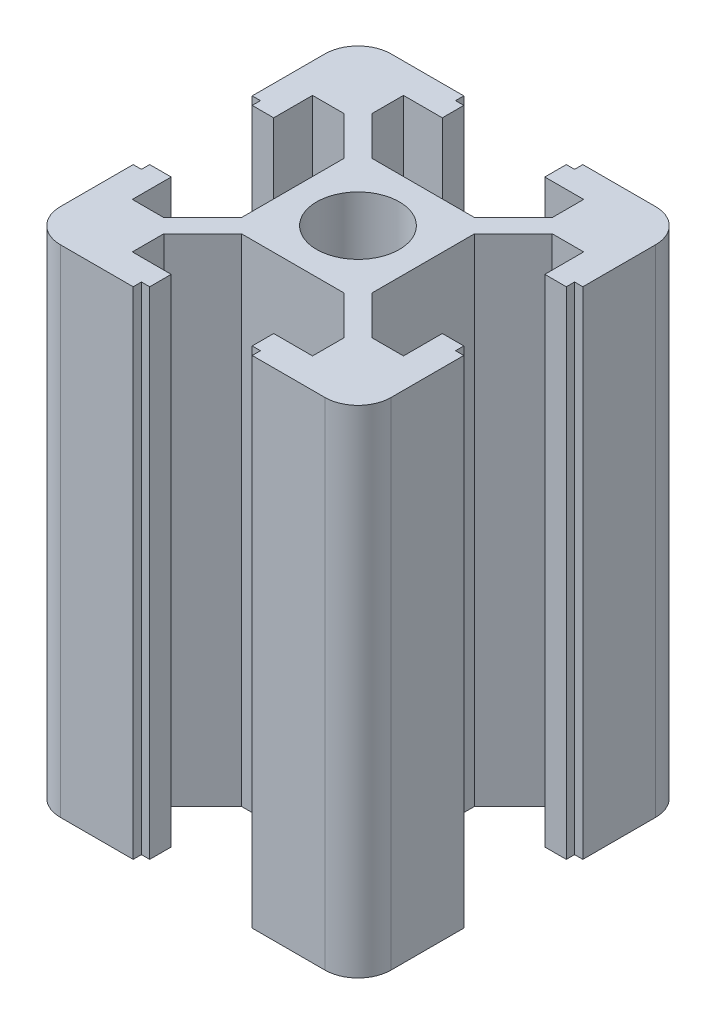
SolidWorks part; units mm, degrees
ref_plane "前视基准面" through (0, 0, 0) normal (0, 0, 1) x (1, 0, 0)
ref_plane "上视基准面" through (0, 0, 0) normal (0, 1, 0) x (1, 0, 0)
ref_plane "右视基准面" through (0, 0, 0) normal (1, 0, 0) x (0, 0, -1)
sketch "草图1" plane through (0, 0, 0) normal (0, 1, 0) x (1, 0, 0)
  line L0 (-6.2985, -5.45) -> (-3.9485, -3.1)
  line L1 (-5.45, -6.2985) -> (-3.1, -3.9485)
  line L2 (-6.2985, -5.45) -> (-8.2, -5.45)
  line L3 (-8.2, -5.45) -> (-8.2, -3.1)
  line L4 (-8.2, -3.1) -> (-10, -3.1)
  line L5 (-10, -3.1) -> (-10, -8)
  line L6 (-8, -10) -> (-3.1, -10)
  line L7 (-5.45, -6.2985) -> (-5.45, -8.2)
  line L8 (-5.45, -8.2) -> (-3.1, -8.2)
  line L9 (-3.1, -8.2) -> (-3.1, -10)
  line L10 (-3.9485, 0) -> (-3.9485, -3.1)
  line L11 (-3.1, -3.9485) -> (0, -3.9485)
  line L12 (-10, -3.6) -> (-9.5, -3.6)
  line L13 (-9.5, -3.6) -> (-9.5, -3.1)
  line L14 (-3.6, -10) -> (-3.6, -9.5)
  line L15 (-3.6, -9.5) -> (-3.1, -9.5)
  line L16 (-3.9485, 0) -> (-2.5, 0) construction
  line L17 (0, -2.5) -> (0, -3.9485) construction
  line L18 (-5.45, 6.2985) -> (-3.1, 3.9485)
  line L19 (-6.2985, 5.45) -> (-3.9485, 3.1)
  line L20 (-5.45, 6.2985) -> (-5.45, 8.2)
  line L21 (-5.45, 8.2) -> (-3.1, 8.2)
  line L22 (-3.1, 8.2) -> (-3.1, 10)
  line L23 (-3.1, 10) -> (-8, 10)
  line L24 (-10, 8) -> (-10, 3.1)
  line L25 (-6.2985, 5.45) -> (-8.2, 5.45)
  line L26 (-8.2, 5.45) -> (-8.2, 3.1)
  line L27 (-8.2, 3.1) -> (-10, 3.1)
  line L28 (-3.1, 3.9485) -> (0, 3.9485)
  line L29 (-3.9485, 3.1) -> (-3.9485, 0)
  line L30 (-3.6, 10) -> (-3.6, 9.5)
  line L31 (-3.6, 9.5) -> (-3.1, 9.5)
  line L32 (-10, 3.6) -> (-9.5, 3.6)
  line L33 (-9.5, 3.6) -> (-9.5, 3.1)
  line L34 (0, 3.9485) -> (0, 2.5) construction
  line L35 (-2.5, 0) -> (-3.9485, 0) construction
  line L36 (6.2985, 5.45) -> (3.9485, 3.1)
  line L37 (5.45, 6.2985) -> (3.1, 3.9485)
  line L38 (6.2985, 5.45) -> (8.2, 5.45)
  line L39 (8.2, 5.45) -> (8.2, 3.1)
  line L40 (8.2, 3.1) -> (10, 3.1)
  line L41 (10, 3.1) -> (10, 8)
  line L42 (8, 10) -> (3.1, 10)
  line L43 (5.45, 6.2985) -> (5.45, 8.2)
  line L44 (5.45, 8.2) -> (3.1, 8.2)
  line L45 (3.1, 8.2) -> (3.1, 10)
  line L46 (3.9485, 0) -> (3.9485, 3.1)
  line L47 (3.1, 3.9485) -> (0, 3.9485)
  line L48 (10, 3.6) -> (9.5, 3.6)
  line L49 (9.5, 3.6) -> (9.5, 3.1)
  line L50 (3.6, 10) -> (3.6, 9.5)
  line L51 (3.6, 9.5) -> (3.1, 9.5)
  line L52 (3.9485, 0) -> (2.5, 0) construction
  line L53 (0, 2.5) -> (0, 3.9485) construction
  line L54 (5.45, -6.2985) -> (3.1, -3.9485)
  line L55 (6.2985, -5.45) -> (3.9485, -3.1)
  line L56 (5.45, -6.2985) -> (5.45, -8.2)
  line L57 (5.45, -8.2) -> (3.1, -8.2)
  line L58 (3.1, -8.2) -> (3.1, -10)
  line L59 (3.1, -10) -> (8, -10)
  line L60 (10, -8) -> (10, -3.1)
  line L61 (6.2985, -5.45) -> (8.2, -5.45)
  line L62 (8.2, -5.45) -> (8.2, -3.1)
  line L63 (8.2, -3.1) -> (10, -3.1)
  line L64 (0, -3.9485) -> (3.1, -3.9485)
  line L65 (3.9485, -3.1) -> (3.9485, 0)
  line L66 (3.6, -10) -> (3.6, -9.5)
  line L67 (3.6, -9.5) -> (3.1, -9.5)
  line L68 (10, -3.6) -> (9.5, -3.6)
  line L69 (9.5, -3.6) -> (9.5, -3.1)
  line L70 (0, -3.9485) -> (0, -2.5) construction
  line L71 (2.5, 0) -> (3.9485, 0) construction
  line L72 (0, 3.9485) -> (-3.1, 3.9485) [skipped]
  circle A0 centre (0, 0) radius 2.5
  arc A1 (-10, -8) -> (-8, -10) centre (-8, -8) ccw
  arc A3 (-8, 10) -> (-10, 8) centre (-8, 8) ccw
  arc A5 (10, 8) -> (8, 10) centre (8, 8) ccw
  arc A7 (8, -10) -> (10, -8) centre (8, -8) ccw
  point P25 (-10, -10)
  point P98 (0, 0)
  dimension "D9" = 2
  dimension "D15" = 5
  dimension "D2" = 1.2
  dimension "D4" = 5.45
  dimension "D5" = 1.8
  dimension "D6" = 3.1
  dimension "D7" = 135
  dimension "D10" = 0.5
  dimension "D11" = 0.5
  dimension "D12" = 0.5
  dimension "D13" = 0.5
  dimension "D14" = 4
extrude "凸台-拉伸1" add sketch "草图1" along normal blind 30 contours L59 A7 L60 L68 L69 L63 L62 L61 L55 L65 L46 L36 L38 L39 L40 L49 L48 L41 A5 L42 L50 L51 L45 L44 L43 L37 L47 L28 L18 L20 L21 L22 L31 L30 L23 A3 L24 L32 L33 L27 L26 L25 L19 L29 L10 L0 L2 L3 L4 L13 L12
